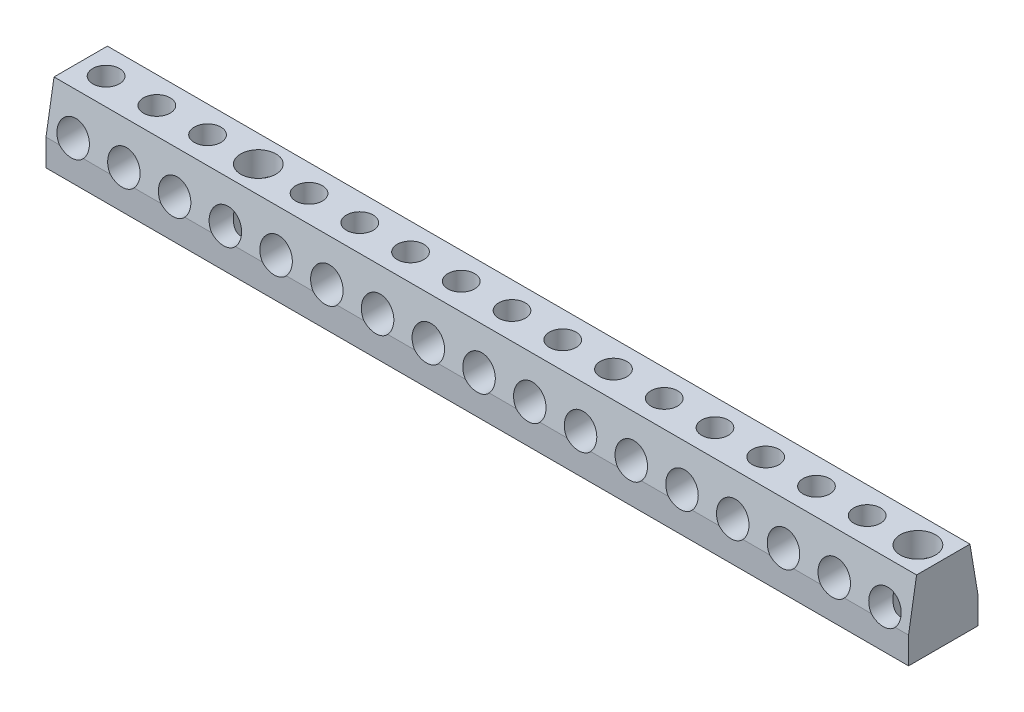
SolidWorks part; units mm, degrees
material "Plain Carbon Steel"
ref_plane "Front Plane" through (0, 0, 0) normal (0, 0, 1) x (1, 0, 0)
ref_plane "Top Plane" through (0, 0, 0) normal (0, 1, 0) x (1, 0, 0)
ref_plane "Right Plane" through (0, 0, 0) normal (1, 0, 0) x (0, 0, -1)
sketch "Sketch1" plane through (0, 0, 0) normal (1, 0, 0) x (0, 0, -1)
  line L0 (6.5, 0) -> (-6.5, 0)
  line L4 (6.5, 0) -> (6.5, 5)
  line L5 (6.5, 5) -> (5, 14)
  line L6 (5, 14) -> (-5, 14)
  line L7 (-5, 14) -> (-6.5, 5)
  line L8 (-6.5, 5) -> (-6.5, 0)
  dimension "D1" = 13
  dimension "D2" = 14
  dimension "D3" = 10
  dimension "D4" = 5
extrude "Boss-Extrude1" add sketch "Sketch1" along normal mid plane 161.5
sketch "Sketch2" plane through (0, 0, 0) normal (0, 0, 1) x (1, 0, 0)
  line L0 (-80.75, 14) -> (-80.75, 5) construction
  line L1 (80.75, 0) -> (-80.75, 0) construction
  circle A0 centre (-76, 7) radius 3
  dimension "D1" = 6
  dimension "D2" = 4.75
  dimension "D3" = 7
extrude "Cut-Extrude1" cut sketch "Sketch2" against normal through all both and the other way through all
hole_wizard "M6x1.0 Tapped Hole1" positions "Sketch3" profile "Sketch4" tap size "M6x1.0" standard "ANSI Metric"
sketch "Sketch3" plane through (0, 14, 0) normal (0, 1, 0) x (1, 0, 0)
  line L0 (-7.7, 0) -> (7.7, 0) construction
  point P0 (-76, 0)
sketch "Sketch4" plane through (-76, 14, 0) normal (1, 0, 0) x (0, 0, 1)
  line L0 (0, 0) -> (0, 4)
  line L1 (0, 4) -> (2.5, 4)
  line L2 (2.5, 4) -> (2.5, 0)
  line L5 (2.5, 0) -> (0, 0)
  line L11 (0, -6.35) -> (0, 107.95) construction
  dimension "Thru Tap Drill Dia." = 5
  dimension "Thru Tap Drill Depth" = 4
cosmetic thread "Hole Thread1" parameters "D2"=6
pattern_linear "LPattern1" count 17 spacing 9.5 along (1, 0, 0) of "Cut-Extrude1", "M6x1.0 Tapped Hole1"
cosmetic thread "Hole Thread2" parameters "D2"=6
cosmetic thread "Hole Thread3" parameters "D2"=6
cosmetic thread "Hole Thread4" parameters "D2"=6
cosmetic thread "Hole Thread5" parameters "D2"=6
cosmetic thread "Hole Thread6" parameters "D2"=6
cosmetic thread "Hole Thread7" parameters "D2"=6
cosmetic thread "Hole Thread8" parameters "D2"=6
cosmetic thread "Hole Thread9" parameters "D2"=6
cosmetic thread "Hole Thread10" parameters "D2"=6
cosmetic thread "Hole Thread11" parameters "D2"=6
cosmetic thread "Hole Thread12" parameters "D2"=6
cosmetic thread "Hole Thread13" parameters "D2"=6
cosmetic thread "Hole Thread14" parameters "D2"=6
cosmetic thread "Hole Thread15" parameters "D2"=6
cosmetic thread "Hole Thread16" parameters "D2"=6
cosmetic thread "Hole Thread17" parameters "D2"=6
hole_wizard "M6 Clearance Hole1" positions "Sketch5" profile "Sketch6" hole size "M6" standard "ANSI Metric" end condition through all
sketch "Sketch5" plane through (0, 14, 0) normal (0, 1, 0) x (1, 0, 0)
  point P0 (-47.5, 0)
  point P3 (76, 0)
sketch "Sketch6" plane through (-47.5, 14, 0) normal (1, 0, 0) x (0, 0, 1)
  line L0 (0, 0) -> (0, 14)
  line L1 (0, 14) -> (3.3, 14)
  line L2 (3.3, 14) -> (3.3, 0)
  line L5 (3.3, 0) -> (0, 0)
  line L11 (0, -6.35) -> (0, 107.95) construction
  dimension "Thru Hole Dia." = 6.6
  dimension "Thru Hole Depth" = 14
